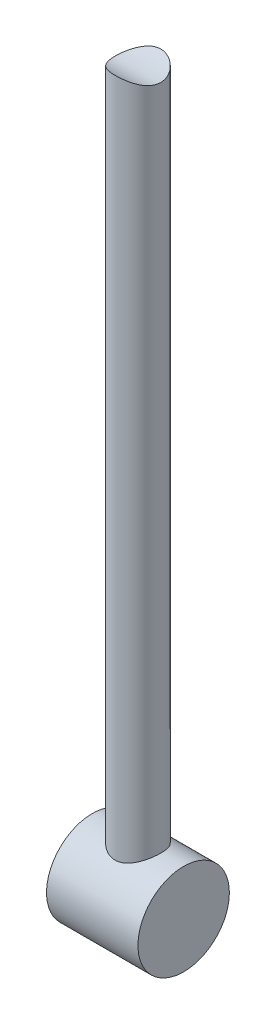
SolidWorks part; units mm, degrees
ref_plane "Front" through (0, 0, 0) normal (0, 0, 1) x (1, 0, 0)
ref_plane "Top" through (0, 0, 0) normal (0, 1, 0) x (1, 0, 0)
ref_plane "Right" through (0, 0, 0) normal (1, 0, 0) x (0, 0, -1)
sketch "Croquis1" plane through (0, 0, 0) normal (1, 0, 0) x (0, 0, -1)
  circle A0 centre (0, 0) radius 50
  dimension "D1" = 100
extrude "Saliente-Extruir1" add sketch "Croquis1" along normal mid plane 100
sketch "Croquis2" plane through (0, 0, 0) normal (0, 1, 0) x (1, 0, 0)
  circle A0 centre (0, 0) radius 25
  dimension "D1" = 50
extrude "Saliente-Extruir2" add sketch "Croquis2" along normal blind 800
sketch "Croquis3" plane through (0, 0, 0) normal (1, 0, 0) x (0, 0, -1)
  line L0 (0, 55) -> (0, -55) construction
  line L1 (25, 800) -> (-25, 800) construction
  circle A0 centre (0, 830) radius 50
  dimension "D1" = 100
  dimension "D2" = 30
extrude "Cortar-Extruir1" cut sketch "Croquis3" against normal through all both and the other way through all
